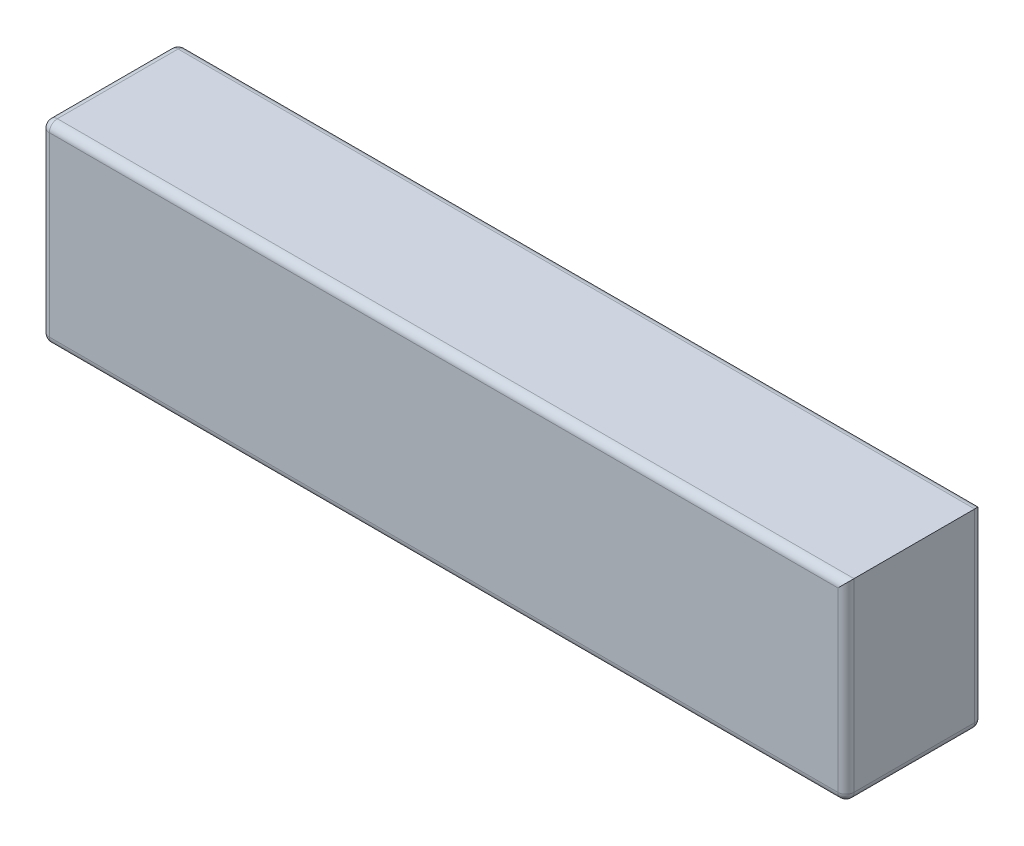
SolidWorks part; units mm, degrees
material "Stainless Steel (ferritic)"
ref_plane "Front Plane" through (0, 0, 0) normal (0, 0, 1) x (1, 0, 0)
ref_plane "Top Plane" through (0, 0, 0) normal (0, 1, 0) x (1, 0, 0)
ref_plane "Right Plane" through (0, 0, 0) normal (1, 0, 0) x (0, 0, -1)
sketch "Sketch1" plane through (0, 0, 0) normal (0, 0, 1) x (1, 0, 0)
  line L1 (-12.7, 3.048) -> (12.7, 3.048)
  line L2 (-12.7, 3.048) -> (-12.7, -3.048)
  line L3 (-12.7, -3.048) -> (12.7, -3.048)
  line L4 (12.7, 3.048) -> (12.7, -3.048)
  line L5 (-12.7, 3.048) -> (12.7, -3.048) construction
  line L6 (-12.7, -3.048) -> (12.7, 3.048) construction
  point P0 (0, 0)
  dimension "D1" = 6.096
extrude "Boss-Extrude1" add sketch "Sketch1" along normal blind 4.318
fillet "Fillet1" radius 0.254 11 edges at (-12.7, 3.048, 2.159) (-12.7, 0, 4.318) (-12.7, -3.048, 2.159) (-12.7, 0, 0) (0, -3.048, 0) (12.7, -3.048, 2.159) (12.7, 0, 0) (12.7, 0, 4.318) (0, -3.048, 4.318) (0, 3.048, 0) (0, 3.048, 4.318)
